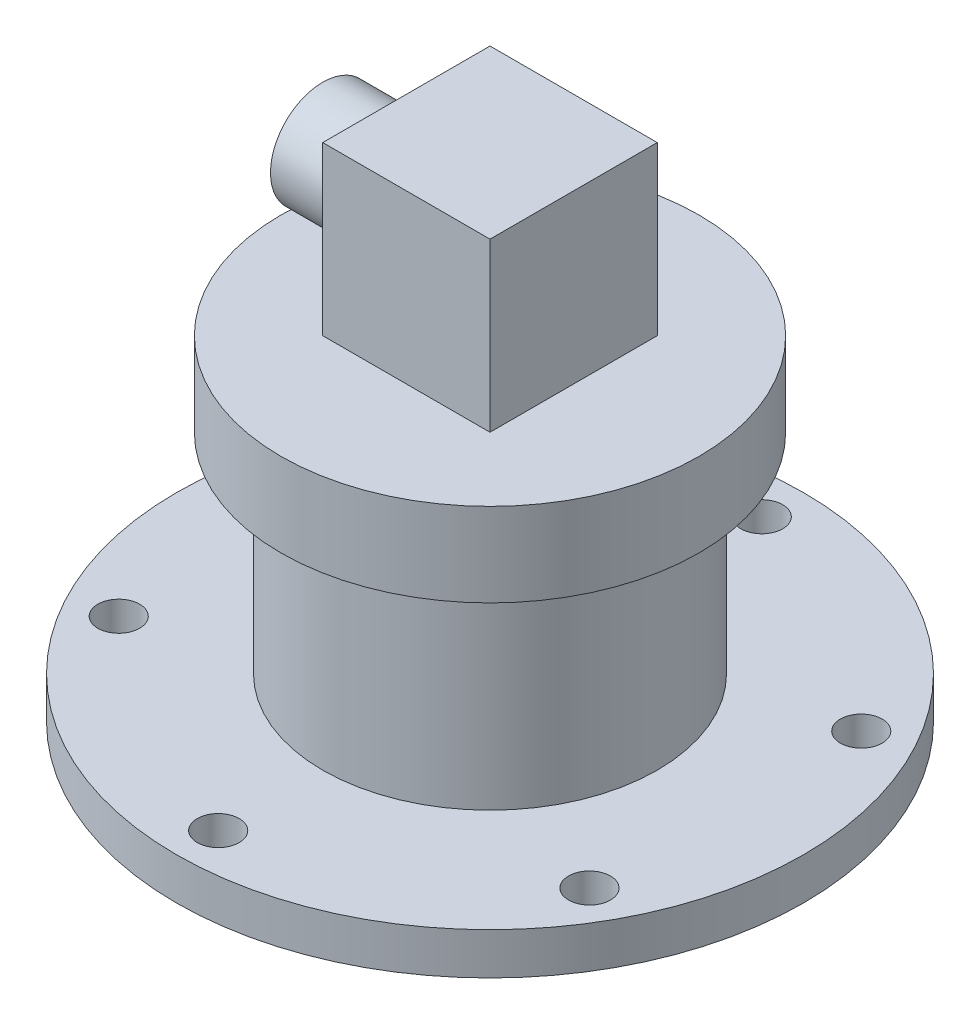
SolidWorks part; units mm, degrees
ref_plane "Front Plane" through (0, 0, 0) normal (0, 0, 1) x (1, 0, 0)
ref_plane "Top Plane" through (0, 0, 0) normal (0, 1, 0) x (1, 0, 0)
ref_plane "Right Plane" through (0, 0, 0) normal (1, 0, 0) x (0, 0, -1)
sketch "Sketch1" plane through (0, 0, 0) normal (0, 1, 0) x (1, 0, 0)
  circle A0 centre (0, 0) radius 75
  dimension "D1" = 150
extrude "Boss-Extrude1" add sketch "Sketch1" along normal blind 10
sketch "Sketch2" plane through (0, 10, 0) normal (0, 1, 0) x (1, 0, 0)
  circle A0 centre (0, 65) radius 5
  circle A1 centre (56.2917, 32.5) radius 5
  circle A2 centre (56.2917, -32.5) radius 5
  circle A3 centre (0, -65) radius 5
  circle A4 centre (-56.2917, -32.5) radius 5
  circle A5 centre (-56.2917, 32.5) radius 5
  point P15 (0, 0)
  dimension "D1" = 10
  dimension "D2" = 65
  dimension "D3" = 6
extrude "Cut-Extrude1" cut sketch "Sketch2" against normal blind 10
sketch "Sketch3" plane through (0, 10, 0) normal (0, 1, 0) x (1, 0, 0)
  circle A0 centre (0, 0) radius 40
  dimension "D1" = 80
extrude "Boss-Extrude2" add sketch "Sketch3" along normal blind 50
sketch "Sketch4" plane through (0, 60, 0) normal (0, 1, 0) x (1, 0, 0)
  circle A0 centre (0, 0) radius 50
  dimension "D1" = 100
extrude "Boss-Extrude3" add sketch "Sketch4" along normal blind 20
sketch "Sketch5" plane through (0, 80, 0) normal (0, 1, 0) x (1, 0, 0)
  line L1 (-20, 20) -> (20, 20)
  line L2 (-20, 20) -> (-20, -20)
  line L3 (-20, -20) -> (20, -20)
  line L4 (20, 20) -> (20, -20)
  line L5 (-20, 20) -> (20, -20) construction
  line L6 (-20, -20) -> (20, 20) construction
  point P0 (0, 0)
  dimension "D1" = 40
  dimension "D2" = 40
extrude "Boss-Extrude4" add sketch "Sketch5" along normal blind 40
sketch "Sketch6" plane through (-20, 0, 0) normal (-1, 0, 0) x (0, 0, 1)
  line L0 (-20, 120) -> (20, 120) construction
  line L1 (-20, 120) -> (-20, 80) construction
  circle A0 centre (0, 100) radius 12.5
  dimension "D1" = 25
  dimension "D2" = 20
  dimension "D3" = 20
extrude "Boss-Extrude5" add sketch "Sketch6" along normal blind 20
sketch "Sketch9" plane through (-40, 0, 0) normal (-1, 0, 0) x (0, 0, 1)
  circle A0 centre (0, 100) radius 7.5
  dimension "D1" = 15
extrude "Cut-Extrude2" cut sketch "Sketch9" against normal blind 15
